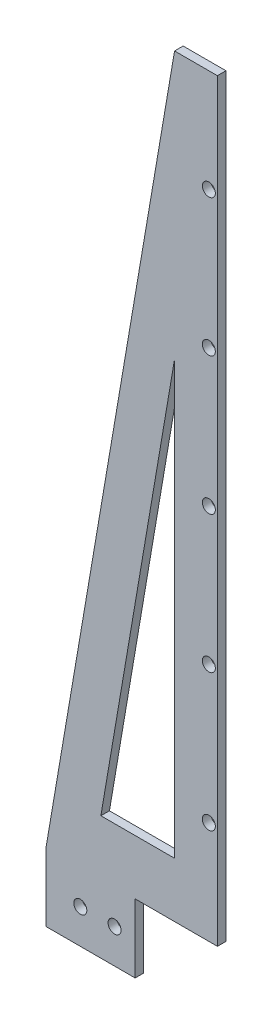
SolidWorks part; units mm, degrees
ref_plane "Front Plane" through (0, 0, 0) normal (0, 0, 1) x (1, 0, 0)
ref_plane "Top Plane" through (0, 0, 0) normal (0, 1, 0) x (1, 0, 0)
ref_plane "Right Plane" through (0, 0, 0) normal (1, 0, 0) x (0, 0, -1)
sketch "Sketch1" plane through (0, 0, 0) normal (0, 0, 1) x (1, 0, 0)
  line L0 (0, 0) -> (33.02, 0)
  line L1 (0, 0) -> (0, 25.4)
  line L2 (63.5, 25.4) -> (63.5, 304.8)
  line L3 (63.5, 304.8) -> (47.625, 304.8)
  line L4 (47.625, 304.8) -> (0, 25.4)
  line L5 (33.02, 0) -> (33.02, 25.4)
  line L6 (33.02, 25.4) -> (63.5, 25.4)
  line L7 (47.625, 205.9093) -> (47.625, 45.72)
  line L8 (47.625, 45.72) -> (20.32, 45.72)
  line L9 (20.32, 45.72) -> (47.625, 205.9093)
  circle A0 centre (12.7, 12.7) radius 2.413
  circle A1 centre (25.4, 12.7) radius 2.413
  circle A3 centre (60.325, 63.5) radius 2.413
  circle A4 centre (60.325, 114.3) radius 2.413
  circle A5 centre (60.325, 165.1) radius 2.413
  circle A6 centre (60.325, 215.9) radius 2.413
  circle A7 centre (60.325, 266.7) radius 2.413
  point P17 (0, 0)
  dimension "D10" = 12.7
  dimension "D11" = 12.7
  dimension "D12" = 4.826
  dimension "D13" = 4.826
  dimension "D14" = 12.7
  dimension "D15" = 7.62
  dimension "D16" = 12.7
  dimension "D17" = 4.826
  dimension "D18" = 38.1
  dimension "D1" = 279.4
  dimension "D2" = 25.4
  dimension "D3" = 33.02
  dimension "D4" = 15.875
  dimension "D5" = 30.48
  dimension "D6" = 25.4
  dimension "D7" = 20.32
  dimension "D8" = 20.32
  dimension "D9" = 180
  dimension "D19" = 5
extrude "Boss-Extrude1" add sketch "Sketch1" along normal blind 3.175 contours L9 L7 L8 | L0 L5 L6 L2 L3 L4 L1 | A0 | A1 | A4 | A3 | A6 | A5 | A7
